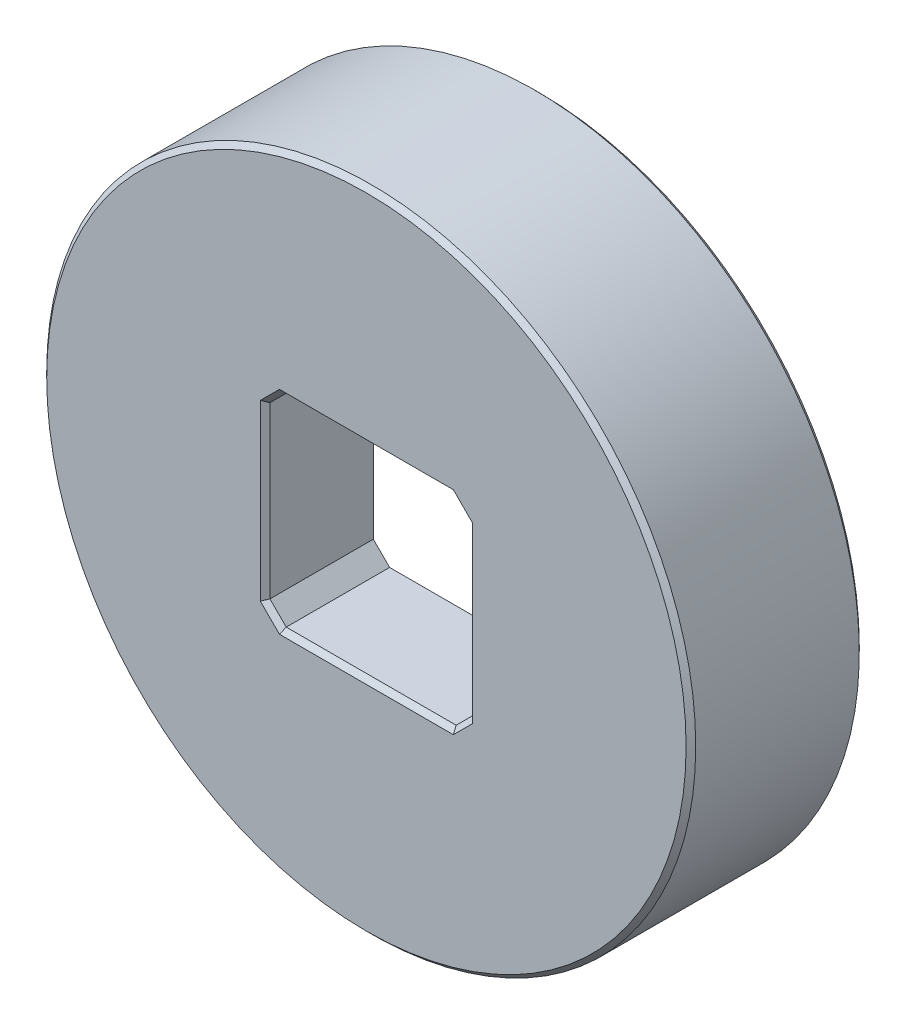
SolidWorks part; units mm, degrees
material "PET"
ref_plane "Front Plane" through (0, 0, 0) normal (0, 0, 1) x (1, 0, 0)
ref_plane "Top Plane" through (0, 0, 0) normal (0, 1, 0) x (1, 0, 0)
ref_plane "Right Plane" through (0, 0, 0) normal (1, 0, 0) x (0, 0, -1)
sketch "Sketch1" plane through (0, 0, 0) normal (0, 0, 1) x (1, 0, 0)
  line L8 (-9.2321, -7.8179) -> (-7.8179, -9.2321)
  line L9 (-9.525, 7.1108) -> (-9.525, -7.1108)
  line L10 (-7.8179, 9.2321) -> (-9.2321, 7.8179)
  line L11 (7.1108, 9.525) -> (-7.1108, 9.525)
  line L12 (9.2321, 7.8179) -> (7.8179, 9.2321)
  line L13 (9.525, -7.1108) -> (9.525, 7.1108)
  line L14 (7.8179, -9.2321) -> (9.2321, -7.8179)
  line L15 (-7.1108, -9.525) -> (7.1108, -9.525)
  line L16 (-9.2321, -7.8179) -> (-7.8179, -9.2321)
  line L17 (-9.525, 7.1108) -> (-9.525, -7.1108)
  line L18 (-7.8179, 9.2321) -> (-9.2321, 7.8179)
  line L19 (7.1108, 9.525) -> (-7.1108, 9.525)
  line L20 (9.2321, 7.8179) -> (7.8179, 9.2321)
  line L21 (9.525, -7.1108) -> (9.525, 7.1108)
  line L22 (7.8179, -9.2321) -> (9.2321, -7.8179)
  line L23 (-7.1108, -9.525) -> (7.1108, -9.525)
  circle A0 centre (0, 0) radius 25 construction
  circle A1 centre (0, 0) radius 25 construction
  circle A2 centre (0, 0) radius 27
  arc A11 (-7.8179, -9.2321) -> (-7.1108, -9.525) centre (-7.1108, -8.525) ccw
  arc A12 (-9.525, -7.1108) -> (-9.2321, -7.8179) centre (-8.525, -7.1108) ccw
  arc A13 (-9.2321, 7.8179) -> (-9.525, 7.1108) centre (-8.525, 7.1108) ccw
  arc A14 (-7.1108, 9.525) -> (-7.8179, 9.2321) centre (-7.1108, 8.525) ccw
  arc A15 (7.8179, 9.2321) -> (7.1108, 9.525) centre (7.1108, 8.525) ccw
  arc A16 (9.525, 7.1108) -> (9.2321, 7.8179) centre (8.525, 7.1108) ccw
  arc A17 (9.2321, -7.8179) -> (9.525, -7.1108) centre (8.525, -7.1108) ccw
  arc A18 (7.1108, -9.525) -> (7.8179, -9.2321) centre (7.1108, -8.525) ccw
  arc A19 (-7.8179, -9.2321) -> (-7.1108, -9.525) centre (-7.1108, -8.525) ccw
  arc A20 (-9.525, -7.1108) -> (-9.2321, -7.8179) centre (-8.525, -7.1108) ccw
  arc A21 (-9.2321, 7.8179) -> (-9.525, 7.1108) centre (-8.525, 7.1108) ccw
  arc A22 (-7.1108, 9.525) -> (-7.8179, 9.2321) centre (-7.1108, 8.525) ccw
  arc A23 (7.8179, 9.2321) -> (7.1108, 9.525) centre (7.1108, 8.525) ccw
  arc A24 (9.525, 7.1108) -> (9.2321, 7.8179) centre (8.525, 7.1108) ccw
  arc A25 (9.2321, -7.8179) -> (9.525, -7.1108) centre (8.525, -7.1108) ccw
  arc A26 (7.1108, -9.525) -> (7.8179, -9.2321) centre (7.1108, -8.525) ccw
  dimension "D1" = 2
  dimension "D2" = 0
extrude "Boss-Extrude1" add sketch "Sketch1" along normal blind 2
sketch "Sketch2" plane through (0, 0, 0) normal (0, 0, -1) x (-1, 0, 0)
  circle A0 centre (0, 0) radius 25 construction
  circle A1 centre (0, 0) radius 27 construction
  circle A2 centre (0, 0) radius 25
  circle A3 centre (0, 0) radius 27
extrude "Boss-Extrude2" add sketch "Sketch2" along normal up to surface (12.41 mm away)
sketch "Sketch3" plane through (0, 0, 2) normal (0, 0, 1) x (1, 0, 0)
  line L0 (-7.0694, -8.425) -> (7.0694, -8.425)
  line L1 (7.0694, -8.425) -> (8.425, -7.0694)
  line L2 (8.425, -7.0694) -> (8.425, 7.0694)
  line L3 (8.425, 7.0694) -> (7.0694, 8.425)
  line L4 (7.0694, 8.425) -> (-7.0694, 8.425)
  line L5 (-7.0694, 8.425) -> (-8.425, 7.0694)
  line L6 (-8.425, 7.0694) -> (-8.425, -7.0694)
  line L7 (-8.425, -7.0694) -> (-7.0694, -8.425)
  line L9 (-7.1108, -9.525) -> (7.1108, -9.525)
  line L10 (-9.2321, -7.8179) -> (-7.8179, -9.2321)
  line L11 (-9.525, 7.1108) -> (-9.525, -7.1108)
  line L12 (-7.8179, 9.2321) -> (-9.2321, 7.8179)
  line L13 (7.1108, 9.525) -> (-7.1108, 9.525)
  line L14 (9.2321, 7.8179) -> (7.8179, 9.2321)
  line L15 (9.525, -7.1108) -> (9.525, 7.1108)
  line L16 (7.8179, -9.2321) -> (9.2321, -7.8179)
  line L17 (-7.1108, -9.525) -> (7.1108, -9.525)
  line L18 (-9.2321, -7.8179) -> (-7.8179, -9.2321)
  line L19 (-9.525, 7.1108) -> (-9.525, -7.1108)
  line L20 (-7.8179, 9.2321) -> (-9.2321, 7.8179)
  line L21 (7.1108, 9.525) -> (-7.1108, 9.525)
  line L22 (9.2321, 7.8179) -> (7.8179, 9.2321)
  line L23 (9.525, -7.1108) -> (9.525, 7.1108)
  line L24 (7.8179, -9.2321) -> (9.2321, -7.8179)
  arc A0 (7.0694, -8.425) -> (7.0694, -8.425) centre (7.0694, -8.425) ccw
  arc A1 (8.425, -7.0694) -> (8.425, -7.0694) centre (8.425, -7.0694) ccw
  arc A2 (8.425, 7.0694) -> (8.425, 7.0694) centre (8.425, 7.0694) ccw
  arc A3 (7.0694, 8.425) -> (7.0694, 8.425) centre (7.0694, 8.425) ccw
  arc A4 (-7.0694, 8.425) -> (-7.0694, 8.425) centre (-7.0694, 8.425) ccw
  arc A5 (-8.425, 7.0694) -> (-8.425, 7.0694) centre (-8.425, 7.0694) ccw
  arc A6 (-8.425, -7.0694) -> (-8.425, -7.0694) centre (-8.425, -7.0694) ccw
  arc A7 (-7.0694, -8.425) -> (-7.0694, -8.425) centre (-7.0694, -8.425) ccw
  arc A8 (-7.8179, -9.2321) -> (-7.1108, -9.525) centre (-7.1108, -8.525) ccw
  arc A9 (-9.525, -7.1108) -> (-9.2321, -7.8179) centre (-8.525, -7.1108) ccw
  arc A10 (-9.2321, 7.8179) -> (-9.525, 7.1108) centre (-8.525, 7.1108) ccw
  arc A11 (-7.1108, 9.525) -> (-7.8179, 9.2321) centre (-7.1108, 8.525) ccw
  arc A12 (7.8179, 9.2321) -> (7.1108, 9.525) centre (7.1108, 8.525) ccw
  arc A13 (9.525, 7.1108) -> (9.2321, 7.8179) centre (8.525, 7.1108) ccw
  arc A14 (9.2321, -7.8179) -> (9.525, -7.1108) centre (8.525, -7.1108) ccw
  arc A15 (7.1108, -9.525) -> (7.8179, -9.2321) centre (7.1108, -8.525) ccw
  arc A16 (-7.8179, -9.2321) -> (-7.1108, -9.525) centre (-7.1108, -8.525) ccw
  arc A17 (-9.525, -7.1108) -> (-9.2321, -7.8179) centre (-8.525, -7.1108) ccw
  arc A18 (-9.2321, 7.8179) -> (-9.525, 7.1108) centre (-8.525, 7.1108) ccw
  arc A19 (-7.1108, 9.525) -> (-7.8179, 9.2321) centre (-7.1108, 8.525) ccw
  arc A20 (7.8179, 9.2321) -> (7.1108, 9.525) centre (7.1108, 8.525) ccw
  arc A21 (9.525, 7.1108) -> (9.2321, 7.8179) centre (8.525, 7.1108) ccw
  arc A22 (9.2321, -7.8179) -> (9.525, -7.1108) centre (8.525, -7.1108) ccw
  arc A23 (7.1108, -9.525) -> (7.8179, -9.2321) centre (7.1108, -8.525) ccw
  dimension "D1" = 0
  dimension "D2" = 1.1
extrude "Boss-Extrude3" add sketch "Sketch3" against normal up to surface (9 mm away)
chamfer "Chamfer1" distance 0.4 angle 45 27 edges at (0, -8.425, 2) (7.7472, -7.7472, 2) (8.425, 0, 2) (7.7472, 7.7472, 2) (0, 8.425, 2) (-7.7472, 7.7472, 2) (-8.425, 0, 2) (-7.7472, -7.7472, 2) (-25, 0, 0) (-9.525, 0, -7) (-9.4489, -7.4935, -7) (-9.4489, 7.4935, -7) (-8.525, -8.525, -7) (-8.525, 8.525, -7) (-7.4935, -9.4489, -7) (-7.4935, 9.4489, -7) (0, -9.525, -7) (0, 9.525, -7) (7.4935, -9.4489, -7) (7.4935, 9.4489, -7) (8.525, -8.525, -7) (8.525, 8.525, -7) (9.4489, -7.4935, -7) (9.4489, 7.4935, -7) (9.525, 0, -7) (-27, 0, -12.41) (27, 0, 2)
